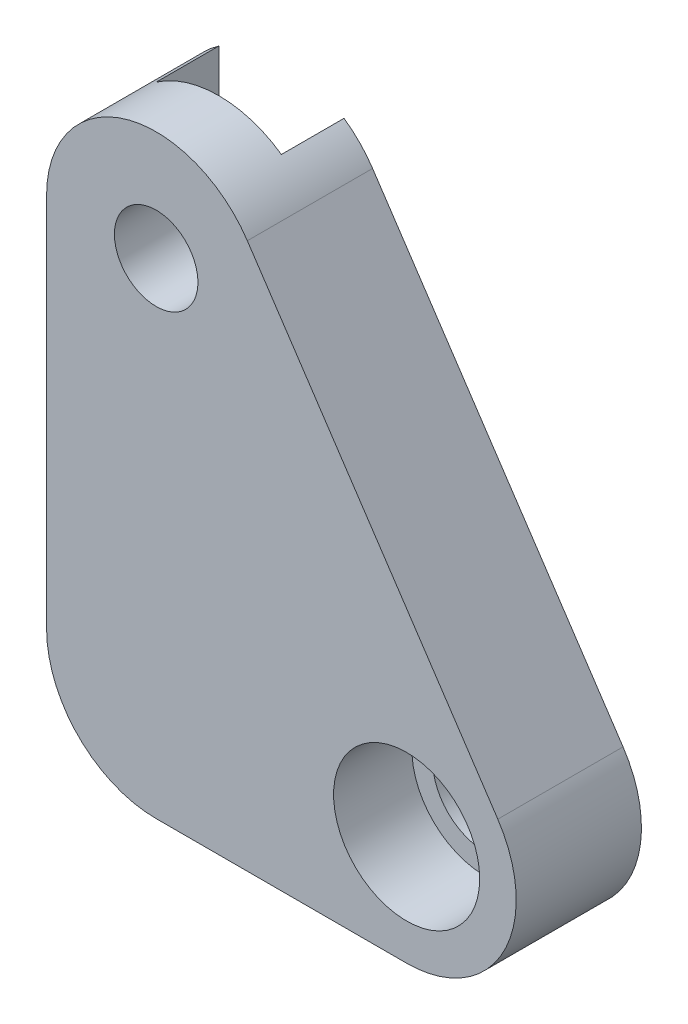
SolidWorks part; units mm, degrees
material "Alliage 1060"
ref_plane "Plan de face" through (0, 0, 0) normal (0, 0, 1) x (1, 0, 0)
ref_plane "Plan de dessus" through (0, 0, 0) normal (0, 1, 0) x (1, 0, 0)
ref_plane "Plan de droite" through (0, 0, 0) normal (1, 0, 0) x (0, 0, -1)
ref_plane "Plan4" through (0, 0, 6) normal (0, 0, -1) x (-1, 0, 0)
sketch "Esquisse1" plane through (0, 0, 6) normal (0, 0, -1) x (-1, 0, 0)
  line L0 (31.05, -21) -> (31.05, 72)
  line L1 (-7.423, 83.6487) -> (-55.423, 11.6487)
  line L2 (-37.95, -21) -> (31.05, -21)
  arc A0 (31.05, 72) -> (-7.423, 83.6487) centre (10.05, 72) ccw
  arc A1 (-55.423, 11.6487) -> (-37.95, -21) centre (-37.95, 0) ccw
extrude "Extrusion1" add sketch "Esquisse1" against normal blind 24
sketch "Esquisse2" plane through (0, -21, 0) normal (0, -1, 0) x (1, 0, 0)
  line L0 (-22.05, 6) -> (1.95, 6)
  line L1 (1.95, 6) -> (1.95, 18)
  line L2 (1.95, 18) -> (-22.05, 18)
  line L3 (-22.05, 18) -> (-22.05, 6)
extrude "Enlèv. mat.-Extru.1" cut sketch "Esquisse2" against normal up to next
hole_wizard "Diamètre du perçage M16.0 (16)1" positions "Esquisse4" profile "Esquisse3" hole size "M16.0" standard "Ansi Métrique"
sketch "Esquisse4" plane through (0, 0, 18) normal (0, 0, -1) x (-1, 0, 0)
  point P0 (10.05, 72)
sketch "Esquisse3" plane through (-10.05, 72, 18) normal (1, 0, 0) x (0, 1, 0)
  line L0 (0, 0) -> (0, 12)
  line L1 (0, 12) -> (8, 12)
  line L2 (8, 12) -> (8, 0)
  line L5 (8, 0) -> (0, 0)
  line L11 (0, -6.35) -> (0, 107.95) construction
  dimension "Diamètre du perçage jusqu'au prochain" = 16
  dimension "Profondeur du perçage jusqu'au prochain" = 12
hole_wizard "Perçage1" positions "Esquisse6" profile "Esquisse5" legacy
sketch "Esquisse6" plane through (0, 0, 30) normal (0, 0, 1) x (1, 0, 0)
  point P0 (37.95, 0)
sketch "Esquisse5" plane through (37.95, 0, 30) normal (1, 0, 0) x (0, -1, 0)
  line L0 (0, 0) -> (0, 24)
  line L1 (0, 24) -> (10, 24)
  line L2 (10, 24) -> (10, 15)
  line L3 (10, 15) -> (14, 15)
  line L4 (14, 15) -> (14, 0)
  line L5 (14, 0) -> (0, 0)
  line L6 (0, 110) -> (0, -10) construction
  dimension "Diamètre" = 20
  dimension "Profondeur" = 24
  dimension "Diamètre chambrage" = 28
  dimension "Profondeur chambrage" = 15
fillet "Congé1" radius 21 1 edges at (-31.05, -21, 18)
sketch "Esquisse7" plane through (0, 0, 6) normal (0, 0, -1) x (-1, 0, 0)
  line L0 (-1.95, 89.2337) -> (-1.95, -21) construction
  line L1 (-1.95, 74.0561) -> (-7.6981, 74.0561)
  line L2 (-1.95, 74.0561) -> (-1.95, 73.1837)
  line L3 (-1.95, 73.1837) -> (-7.6981, 73.1837)
  line L4 (-7.6981, 74.0561) -> (-7.6981, 73.1837)
extrude "Enlèv. mat.-Extru.2" cut sketch "Esquisse7" against normal blind 1
pattern_linear "Répétition linéaire1" count 44 spacing 2 along (0, -1, 0) of "Enlèv. mat.-Extru.2"
